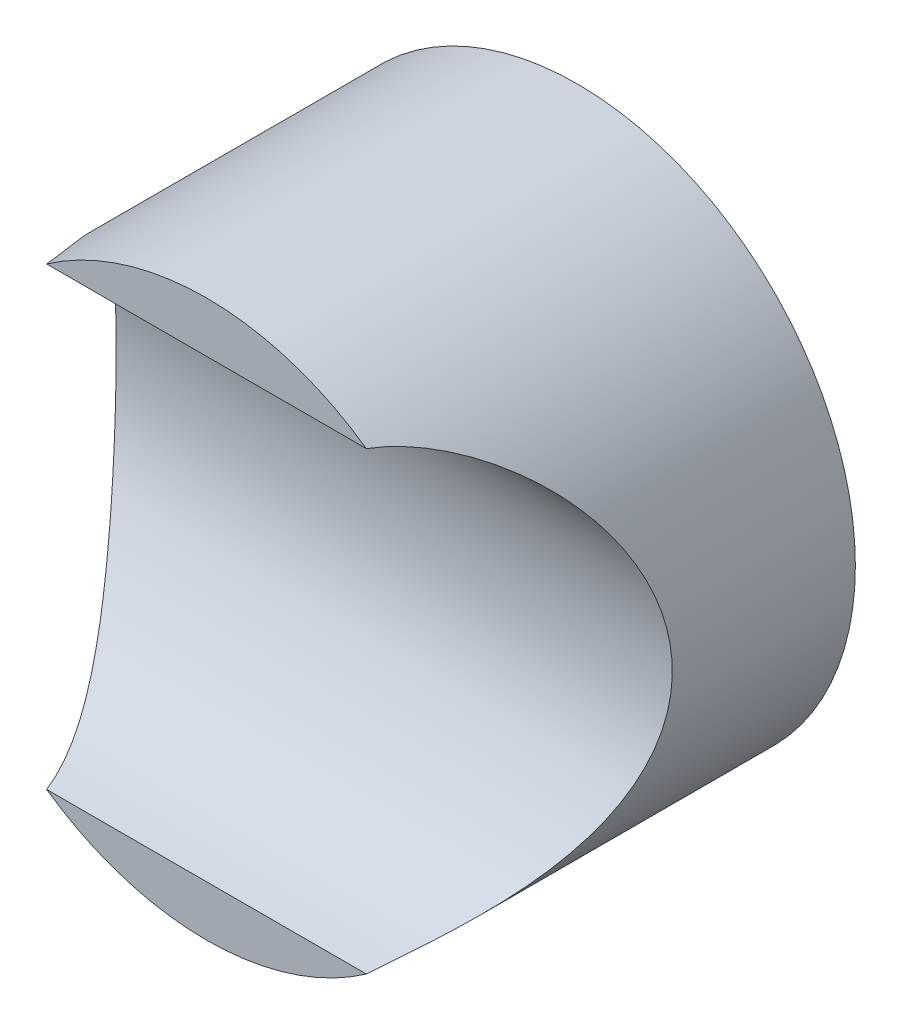
SolidWorks part; units mm, degrees
ref_plane "Płaszczyzna przednia" through (0, 0, 0) normal (0, 0, 1) x (1, 0, 0)
ref_plane "Płaszczyzna górna" through (0, 0, 0) normal (0, 1, 0) x (1, 0, 0)
ref_plane "Płaszczyzna prawa" through (0, 0, 0) normal (1, 0, 0) x (0, 0, -1)
sketch "Szkic1" plane through (0, 0, 0) normal (0, 0, 1) x (1, 0, 0)
  circle A0 centre (0, 0) radius 30
extrude "Dodanie-wyciągnięcie1" add sketch "Szkic1" along normal blind 40
sketch "Szkic2" plane through (0, 0, 0) normal (1, 0, 0) x (0, 0, -1)
  line L0 (-40, 30) -> (-40, -30)
  circle A0 centre (-44.7469, 0) radius 25
  dimension "D1" = 50
extrude "Wytnij-wyciągnięcie1" cut sketch "Szkic2" against normal through all both and the other way through all contours L0 A0 | L0 A0
sketch "Szkic4" plane through (0, 0, 0) normal (0, 0, -1) x (-1, 0, 0)
  circle A0 centre (0, 0) radius 10
extrude "Wytnij-wyciągnięcie2" cut sketch "Szkic4" against normal blind 2
